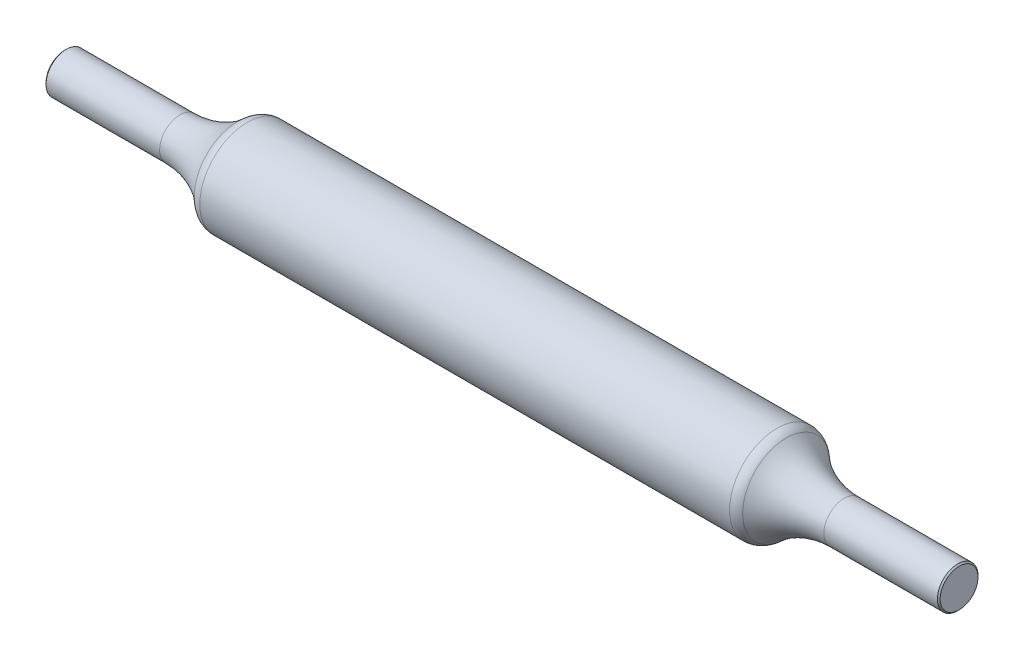
SolidWorks part; units mm, degrees
ref_plane "Front Plane" through (0, 0, 0) normal (0, 0, 1) x (1, 0, 0)
ref_plane "Top Plane" through (0, 0, 0) normal (0, 1, 0) x (1, 0, 0)
ref_plane "Right Plane" through (0, 0, 0) normal (1, 0, 0) x (0, 0, -1)
sketch "Sketch1" plane through (0, 0, 0) normal (0, 0, 1) x (1, 0, 0)
  line L0 (-16.525, 0) -> (16.525, 0)
  line L1 (-16.525, 0) -> (-16.525, 0.75)
  line L2 (-16.525, 0.75) -> (-12.275, 0.75)
  line L3 (16.525, 0) -> (16.525, 0.75)
  line L4 (16.525, 0.75) -> (12.275, 0.75)
  line L5 (-10, 1.75) -> (10, 1.75)
  arc A0 (-12.275, 0.75) -> (-10, 1.75) centre (-12.275, 3.8378) ccw
  arc A1 (10, 1.75) -> (12.275, 0.75) centre (12.275, 3.8378) ccw
  point P2 (0, 0)
  point P10 (0, 1.75)
  dimension "D1" = 33.05
  dimension "D2" = 20
  dimension "D3" = 4.25
  dimension "D4" = 1.75
  dimension "D5" = 0.75
revolve "Revolve1" add sketch "Sketch1" angle 360 about L0
fillet "Fillet1" radius 0.5 2 edges at (-10, -1.75, 0) (10, -1.75, 0)
chamfer "Chamfer1" distance 0.05 angle 45 2 edges at (16.525, -0.75, 0) (-16.525, -0.75, 0)
